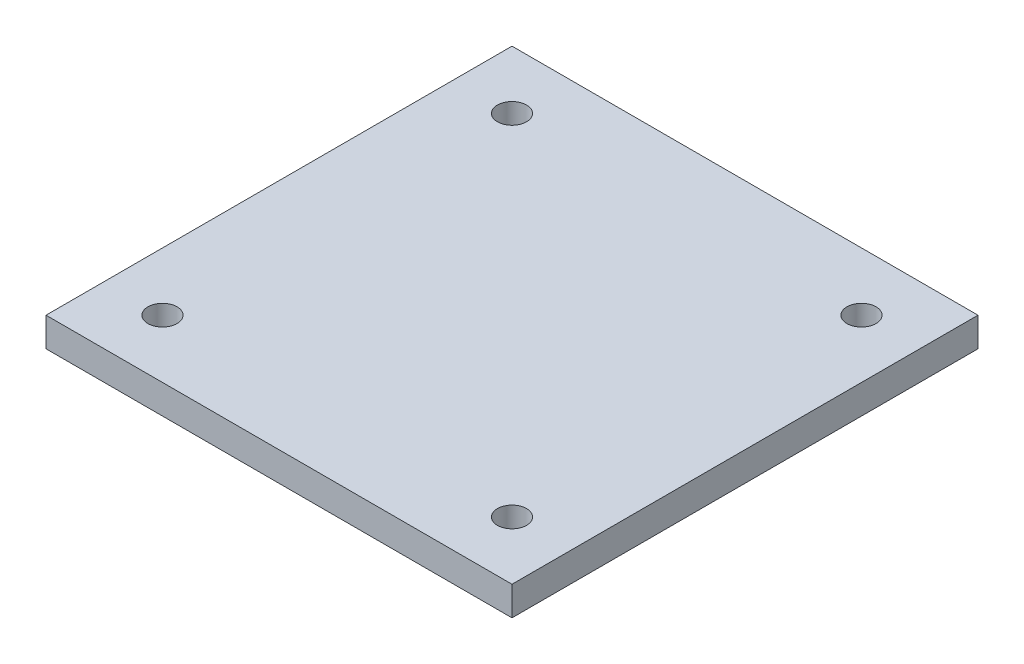
SolidWorks part; units mm, degrees
ref_plane "Front Plane" through (0, 0, 0) normal (0, 0, 1) x (1, 0, 0)
ref_plane "Top Plane" through (0, 0, 0) normal (0, 1, 0) x (1, 0, 0)
ref_plane "Right Plane" through (0, 0, 0) normal (1, 0, 0) x (0, 0, -1)
sketch "Sketch1" plane through (0, 0, 0) normal (0, 1, 0) x (1, 0, 0)
  line L1 (-50.8, -50.8) -> (50.8, -50.8)
  line L2 (-50.8, -50.8) -> (-50.8, 50.8)
  line L3 (-50.8, 50.8) -> (50.8, 50.8)
  line L4 (50.8, -50.8) -> (50.8, 50.8)
  line L5 (-50.8, -50.8) -> (50.8, 50.8) construction
  line L6 (-50.8, 50.8) -> (50.8, -50.8) construction
  circle A0 centre (-38.1, 38.1) radius 3.175
  circle A1 centre (38.1, 38.1) radius 3.175
  circle A2 centre (38.1, -38.1) radius 3.175
  circle A3 centre (-38.1, -38.1) radius 3.175
  point P0 (0, 0)
  dimension "D3" = 6.35
  dimension "D1" = 101.6
  dimension "D2" = 101.6
  dimension "D4" = 12.7
  dimension "D5" = 12.7
  dimension "D6" = 2
  dimension "D7" = 2
extrude "Boss-Extrude1" add sketch "Sketch1" along normal blind 6.35
